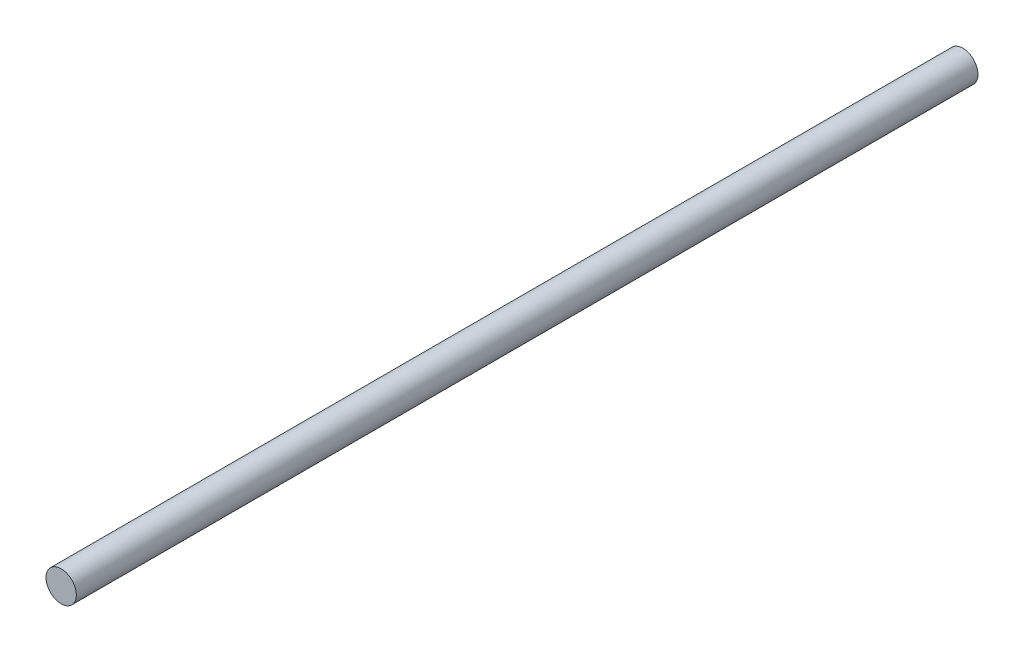
SolidWorks part; units mm, degrees
ref_plane "Front Plane" through (0, 0, 0) normal (0, 0, 1) x (1, 0, 0)
ref_plane "Top Plane" through (0, 0, 0) normal (0, 1, 0) x (1, 0, 0)
ref_plane "Right Plane" through (0, 0, 0) normal (1, 0, 0) x (0, 0, -1)
sketch "Sketch1" plane through (0, 0, 0) normal (0, 0, 1) x (1, 0, 0)
  circle A0 centre (0, 0) radius 2.5
  dimension "D1" = 5
extrude "Boss-Extrude1" add sketch "Sketch1" along normal blind 148.5
